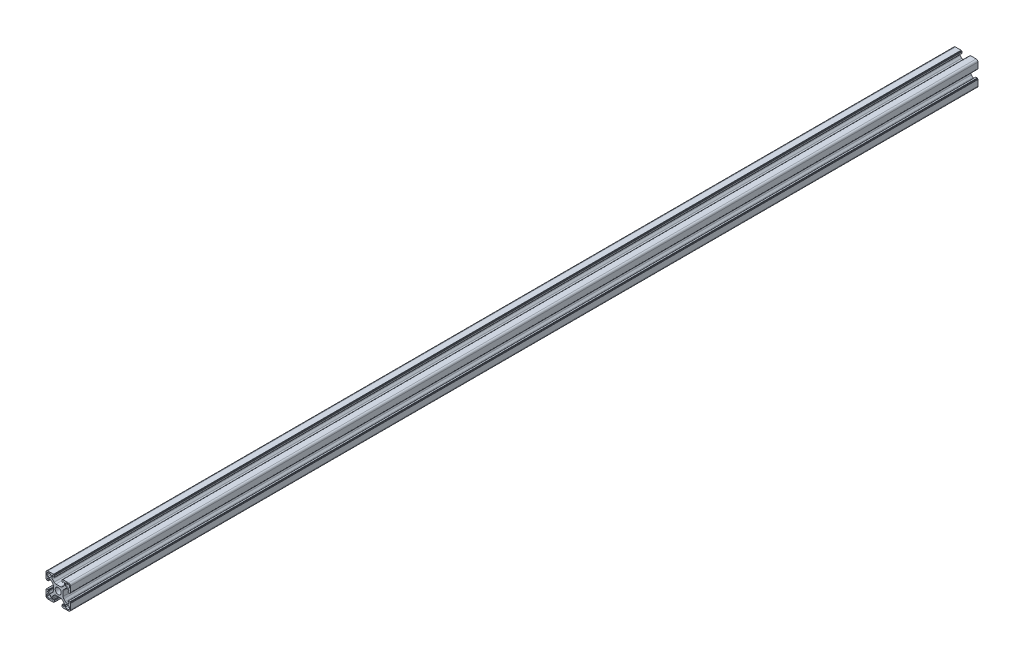
SolidWorks part; units mm, degrees
ref_plane "Спереди" through (0, 0, 0) normal (0, 0, 1) x (1, 0, 0)
ref_plane "Сверху" through (0, 0, 0) normal (0, 1, 0) x (1, 0, 0)
ref_plane "Справа" through (0, 0, 0) normal (1, 0, 0) x (0, 0, -1)
sketch "Эскиз1" plane through (0, 0, 0) normal (0, 0, 1) x (1, 0, 0)
  line L0 (-9.367, 48.5619) -> (-12.367, 45.5619) construction
  line L1 (-18.467, 43.4619) -> (-16.5682, 43.4619)
  line L2 (-18.467, 39.4619) -> (-8.467, 49.4619) construction
  line L3 (-10.867, 47.0619) -> (-12.367, 48.5619) construction
  line L4 (-15.154, 44.0477) -> (-13.8528, 45.3489)
  line L5 (-11.567, 45.5619) -> (-10.167, 45.5619)
  line L6 (-12.367, 46.3619) -> (-12.367, 47.7619)
  line L7 (-10.167, 48.5619) -> (-11.567, 48.5619)
  line L8 (-13.267, 47.6619) -> (-13.267, 46.7631)
  line L9 (-14.7038, 47.5351) -> (-14.2234, 48.0154)
  line L10 (-15.267, 49.0109) -> (-14.767, 49.0109)
  line L11 (-14.8805, 47.4619) -> (-15.167, 47.4619)
  line L12 (-13.8699, 48.1619) -> (-13.767, 48.1619)
  line L13 (-14.767, 49.3119) -> (-14.767, 49.0109)
  line L14 (-15.417, 48.8609) -> (-15.417, 47.7119)
  line L15 (-9.967, 49.4619) -> (-14.617, 49.4619)
  line L16 (-9.367, 47.7619) -> (-9.367, 46.3619)
  line L17 (-8.467, 47.9619) -> (-8.467, 43.3119)
  line L18 (-9.0679, 42.5119) -> (-10.217, 42.5119)
  line L19 (-8.617, 43.1619) -> (-8.9179, 43.1619)
  line L20 (-9.767, 44.059) -> (-9.767, 44.1619)
  line L21 (-10.467, 43.0483) -> (-10.467, 42.7619)
  line L22 (-8.9179, 42.6619) -> (-8.9179, 43.1619)
  line L23 (-10.3938, 43.2251) -> (-9.9134, 43.7054)
  line L24 (-10.267, 44.6619) -> (-11.1658, 44.6619)
  line L25 (-13.8812, 42.7749) -> (-12.58, 44.0761)
  line L26 (-14.467, 39.4619) -> (-14.467, 41.3607)
  line L27 (-14.467, 39.4619) -> (-14.467, 37.5631)
  line L28 (-13.8812, 36.1489) -> (-12.58, 34.8477)
  line L29 (-12.367, 32.5619) -> (-12.367, 31.1619)
  line L30 (-11.567, 33.3619) -> (-10.167, 33.3619)
  line L31 (-9.367, 31.1619) -> (-9.367, 32.5619)
  line L32 (-10.267, 34.2619) -> (-11.1658, 34.2619)
  line L33 (-10.3938, 35.6987) -> (-9.9134, 35.2183)
  line L34 (-8.9179, 36.2619) -> (-8.9179, 35.7619)
  line L35 (-10.467, 35.8754) -> (-10.467, 36.1619)
  line L36 (-9.767, 34.8648) -> (-9.767, 34.7619)
  line L37 (-8.617, 35.7619) -> (-8.9179, 35.7619)
  line L38 (-9.0679, 36.4119) -> (-10.217, 36.4119)
  line L39 (-8.467, 30.9619) -> (-8.467, 35.6119)
  line L40 (-10.167, 30.3619) -> (-11.567, 30.3619)
  line L41 (-9.967, 29.4619) -> (-14.617, 29.4619)
  line L42 (-15.417, 30.0628) -> (-15.417, 31.2119)
  line L43 (-14.767, 29.6119) -> (-14.767, 29.9128)
  line L44 (-13.8699, 30.7619) -> (-13.767, 30.7619)
  line L45 (-14.8805, 31.4619) -> (-15.167, 31.4619)
  line L46 (-15.267, 29.9128) -> (-14.767, 29.9128)
  line L47 (-14.7038, 31.3887) -> (-14.2234, 30.9083)
  line L48 (-13.267, 31.2619) -> (-13.267, 32.1607)
  line L49 (-15.154, 34.8761) -> (-13.8528, 33.5749)
  line L50 (-18.467, 35.4619) -> (-16.5682, 35.4619)
  line L51 (-9.367, 30.3619) -> (-12.367, 33.3619) construction
  line L52 (-18.467, 39.4619) -> (-8.467, 29.4619) construction
  line L53 (-10.867, 31.8619) -> (-9.367, 33.3619) construction
  line L54 (-18.467, 35.4619) -> (-20.3658, 35.4619)
  line L55 (-21.78, 34.8761) -> (-23.0812, 33.5749)
  line L56 (-25.367, 33.3619) -> (-26.767, 33.3619)
  line L57 (-24.567, 32.5619) -> (-24.567, 31.1619)
  line L58 (-26.767, 30.3619) -> (-25.367, 30.3619)
  line L59 (-23.667, 31.2619) -> (-23.667, 32.1607)
  line L60 (-22.2302, 31.3887) -> (-22.7105, 30.9083)
  line L61 (-21.667, 29.9128) -> (-22.167, 29.9128)
  line L62 (-22.0534, 31.4619) -> (-21.767, 31.4619)
  line L63 (-23.0641, 30.7619) -> (-23.167, 30.7619)
  line L64 (-22.167, 29.6119) -> (-22.167, 29.9128)
  line L65 (-21.517, 30.0628) -> (-21.517, 31.2119)
  line L66 (-26.967, 29.4619) -> (-22.317, 29.4619)
  line L67 (-27.567, 31.1619) -> (-27.567, 32.5619)
  line L68 (-28.467, 30.9619) -> (-28.467, 35.6119)
  line L69 (-27.8661, 36.4119) -> (-26.717, 36.4119)
  line L70 (-28.317, 35.7619) -> (-28.0161, 35.7619)
  line L71 (-27.167, 34.8648) -> (-27.167, 34.7619)
  line L72 (-26.467, 35.8754) -> (-26.467, 36.1619)
  line L73 (-28.0161, 36.2619) -> (-28.0161, 35.7619)
  line L74 (-26.5402, 35.6987) -> (-27.0205, 35.2183)
  line L75 (-26.667, 34.2619) -> (-25.7682, 34.2619)
  line L76 (-23.0528, 36.1489) -> (-24.354, 34.8477)
  line L77 (-22.467, 39.4619) -> (-22.467, 37.5631)
  line L78 (-27.567, 30.3619) -> (-24.567, 33.3619) construction
  line L79 (-18.467, 39.4619) -> (-28.467, 29.4619) construction
  line L80 (-26.067, 31.8619) -> (-24.567, 30.3619) construction
  line L81 (-22.467, 39.4619) -> (-22.467, 41.3607)
  line L82 (-23.0528, 42.7749) -> (-24.354, 44.0761)
  line L83 (-24.567, 46.3619) -> (-24.567, 47.7619)
  line L84 (-25.367, 45.5619) -> (-26.767, 45.5619)
  line L85 (-27.567, 47.7619) -> (-27.567, 46.3619)
  line L86 (-26.667, 44.6619) -> (-25.7682, 44.6619)
  line L87 (-26.5402, 43.2251) -> (-27.0205, 43.7054)
  line L88 (-28.0161, 42.6619) -> (-28.0161, 43.1619)
  line L89 (-26.467, 43.0483) -> (-26.467, 42.7619)
  line L90 (-27.167, 44.059) -> (-27.167, 44.1619)
  line L91 (-28.317, 43.1619) -> (-28.0161, 43.1619)
  line L92 (-27.8661, 42.5119) -> (-26.717, 42.5119)
  line L93 (-28.467, 47.9619) -> (-28.467, 43.3119)
  line L94 (-26.767, 48.5619) -> (-25.367, 48.5619)
  line L95 (-26.967, 49.4619) -> (-22.317, 49.4619)
  line L96 (-21.517, 48.8609) -> (-21.517, 47.7119)
  line L97 (-22.167, 49.3119) -> (-22.167, 49.0109)
  line L98 (-23.0641, 48.1619) -> (-23.167, 48.1619)
  line L99 (-22.0534, 47.4619) -> (-21.767, 47.4619)
  line L100 (-21.667, 49.0109) -> (-22.167, 49.0109)
  line L101 (-22.2302, 47.5351) -> (-22.7105, 48.0154)
  line L102 (-23.667, 47.6619) -> (-23.667, 46.7631)
  line L103 (-21.78, 44.0477) -> (-23.0812, 45.3489)
  line L104 (-18.467, 43.4619) -> (-20.3658, 43.4619)
  line L105 (-30.231, 39.4619) -> (-6.9626, 39.4619) construction
  line L106 (-27.567, 48.5619) -> (-24.567, 45.5619) construction
  line L107 (-18.467, 27.3755) -> (-18.467, 50.1808) construction
  line L108 (-18.467, 39.4619) -> (-28.467, 49.4619) construction
  line L109 (-26.067, 47.0619) -> (-27.567, 45.5619) construction
  arc A0 (-9.367, 47.7619) -> (-10.167, 48.5619) centre (-10.167, 47.7619) ccw
  arc A1 (-11.567, 48.5619) -> (-12.367, 47.7619) centre (-11.567, 47.7619) ccw
  arc A2 (-11.567, 45.5619) -> (-12.367, 46.3619) centre (-11.567, 46.3619) cw
  arc A3 (-9.967, 49.4619) -> (-8.467, 47.9619) centre (-9.967, 47.9619) cw
  arc A4 (-15.267, 49.0109) -> (-15.417, 48.8609) centre (-15.267, 48.8609) ccw
  arc A5 (-14.617, 49.4619) -> (-14.767, 49.3119) centre (-14.617, 49.3119) ccw
  arc A6 (-14.8805, 47.4619) -> (-14.7038, 47.5351) centre (-14.8805, 47.7119) ccw
  arc A7 (-15.167, 47.4619) -> (-15.417, 47.7119) centre (-15.167, 47.7119) cw
  arc A8 (-14.2234, 48.0154) -> (-13.8699, 48.1619) centre (-13.8699, 47.6619) cw
  arc A9 (-13.767, 48.1619) -> (-13.267, 47.6619) centre (-13.767, 47.6619) cw
  arc A10 (-15.967, 39.4619) -> (-18.467, 41.9619) centre (-18.467, 39.4619) ccw
  arc A11 (-16.5682, 43.4619) -> (-15.154, 44.0477) centre (-16.5682, 45.4619) ccw
  arc A12 (-13.267, 46.7631) -> (-13.8528, 45.3489) centre (-15.267, 46.7631) cw
  arc A13 (-9.367, 46.3619) -> (-10.167, 45.5619) centre (-10.167, 46.3619) cw
  arc A14 (-9.767, 44.1619) -> (-10.267, 44.6619) centre (-10.267, 44.1619) ccw
  arc A15 (-9.9134, 43.7054) -> (-9.767, 44.059) centre (-10.267, 44.059) ccw
  arc A16 (-10.467, 42.7619) -> (-10.217, 42.5119) centre (-10.217, 42.7619) ccw
  arc A17 (-10.467, 43.0483) -> (-10.3938, 43.2251) centre (-10.217, 43.0483) cw
  arc A18 (-8.467, 43.3119) -> (-8.617, 43.1619) centre (-8.617, 43.3119) cw
  arc A19 (-8.9179, 42.6619) -> (-9.0679, 42.5119) centre (-9.0679, 42.6619) cw
  arc A20 (-11.1658, 44.6619) -> (-12.58, 44.0761) centre (-11.1658, 42.6619) ccw
  arc A21 (-14.467, 41.3607) -> (-13.8812, 42.7749) centre (-12.467, 41.3607) cw
  arc A22 (-10.167, 30.3619) -> (-9.367, 31.1619) centre (-10.167, 31.1619) ccw
  arc A23 (-9.367, 32.5619) -> (-10.167, 33.3619) centre (-10.167, 32.5619) ccw
  arc A24 (-12.367, 32.5619) -> (-11.567, 33.3619) centre (-11.567, 32.5619) cw
  arc A25 (-8.467, 30.9619) -> (-9.967, 29.4619) centre (-9.967, 30.9619) cw
  arc A26 (-8.9179, 36.2619) -> (-9.0679, 36.4119) centre (-9.0679, 36.2619) ccw
  arc A27 (-8.467, 35.6119) -> (-8.617, 35.7619) centre (-8.617, 35.6119) ccw
  arc A28 (-10.467, 35.8754) -> (-10.3938, 35.6987) centre (-10.217, 35.8754) ccw
  arc A29 (-10.467, 36.1619) -> (-10.217, 36.4119) centre (-10.217, 36.1619) cw
  arc A30 (-9.9134, 35.2183) -> (-9.767, 34.8648) centre (-10.267, 34.8648) cw
  arc A31 (-9.767, 34.7619) -> (-10.267, 34.2619) centre (-10.267, 34.7619) cw
  arc A32 (-18.467, 36.9619) -> (-15.967, 39.4619) centre (-18.467, 39.4619) ccw
  arc A33 (-14.467, 37.5631) -> (-13.8812, 36.1489) centre (-12.467, 37.5631) ccw
  arc A34 (-11.1658, 34.2619) -> (-12.58, 34.8477) centre (-11.1658, 36.2619) cw
  arc A35 (-11.567, 30.3619) -> (-12.367, 31.1619) centre (-11.567, 31.1619) cw
  arc A36 (-13.767, 30.7619) -> (-13.267, 31.2619) centre (-13.767, 31.2619) ccw
  arc A37 (-14.2234, 30.9083) -> (-13.8699, 30.7619) centre (-13.8699, 31.2619) ccw
  arc A38 (-15.167, 31.4619) -> (-15.417, 31.2119) centre (-15.167, 31.2119) ccw
  arc A39 (-14.8805, 31.4619) -> (-14.7038, 31.3887) centre (-14.8805, 31.2119) cw
  arc A40 (-14.617, 29.4619) -> (-14.767, 29.6119) centre (-14.617, 29.6119) cw
  arc A41 (-15.267, 29.9128) -> (-15.417, 30.0628) centre (-15.267, 30.0628) cw
  arc A42 (-13.267, 32.1607) -> (-13.8528, 33.5749) centre (-15.267, 32.1607) ccw
  arc A43 (-16.5682, 35.4619) -> (-15.154, 34.8761) centre (-16.5682, 33.4619) cw
  arc A44 (-27.567, 31.1619) -> (-26.767, 30.3619) centre (-26.767, 31.1619) ccw
  arc A45 (-25.367, 30.3619) -> (-24.567, 31.1619) centre (-25.367, 31.1619) ccw
  arc A46 (-25.367, 33.3619) -> (-24.567, 32.5619) centre (-25.367, 32.5619) cw
  arc A47 (-26.967, 29.4619) -> (-28.467, 30.9619) centre (-26.967, 30.9619) cw
  arc A48 (-21.667, 29.9128) -> (-21.517, 30.0628) centre (-21.667, 30.0628) ccw
  arc A49 (-22.317, 29.4619) -> (-22.167, 29.6119) centre (-22.317, 29.6119) ccw
  arc A50 (-22.0534, 31.4619) -> (-22.2302, 31.3887) centre (-22.0534, 31.2119) ccw
  arc A51 (-21.767, 31.4619) -> (-21.517, 31.2119) centre (-21.767, 31.2119) cw
  arc A52 (-22.7105, 30.9083) -> (-23.0641, 30.7619) centre (-23.0641, 31.2619) cw
  arc A53 (-23.167, 30.7619) -> (-23.667, 31.2619) centre (-23.167, 31.2619) cw
  arc A54 (-20.967, 39.4619) -> (-18.467, 36.9619) centre (-18.467, 39.4619) ccw
  arc A55 (-20.3658, 35.4619) -> (-21.78, 34.8761) centre (-20.3658, 33.4619) ccw
  arc A56 (-23.667, 32.1607) -> (-23.0812, 33.5749) centre (-21.667, 32.1607) cw
  arc A57 (-27.567, 32.5619) -> (-26.767, 33.3619) centre (-26.767, 32.5619) cw
  arc A58 (-27.167, 34.7619) -> (-26.667, 34.2619) centre (-26.667, 34.7619) ccw
  arc A59 (-27.0205, 35.2183) -> (-27.167, 34.8648) centre (-26.667, 34.8648) ccw
  arc A60 (-26.467, 36.1619) -> (-26.717, 36.4119) centre (-26.717, 36.1619) ccw
  arc A61 (-26.467, 35.8754) -> (-26.5402, 35.6987) centre (-26.717, 35.8754) cw
  arc A62 (-28.467, 35.6119) -> (-28.317, 35.7619) centre (-28.317, 35.6119) cw
  arc A63 (-28.0161, 36.2619) -> (-27.8661, 36.4119) centre (-27.8661, 36.2619) cw
  arc A64 (-25.7682, 34.2619) -> (-24.354, 34.8477) centre (-25.7682, 36.2619) ccw
  arc A65 (-22.467, 37.5631) -> (-23.0528, 36.1489) centre (-24.467, 37.5631) cw
  arc A66 (-26.767, 48.5619) -> (-27.567, 47.7619) centre (-26.767, 47.7619) ccw
  arc A67 (-27.567, 46.3619) -> (-26.767, 45.5619) centre (-26.767, 46.3619) ccw
  arc A68 (-24.567, 46.3619) -> (-25.367, 45.5619) centre (-25.367, 46.3619) cw
  arc A69 (-28.467, 47.9619) -> (-26.967, 49.4619) centre (-26.967, 47.9619) cw
  arc A70 (-28.0161, 42.6619) -> (-27.8661, 42.5119) centre (-27.8661, 42.6619) ccw
  arc A71 (-28.467, 43.3119) -> (-28.317, 43.1619) centre (-28.317, 43.3119) ccw
  arc A72 (-26.467, 43.0483) -> (-26.5402, 43.2251) centre (-26.717, 43.0483) ccw
  arc A73 (-26.467, 42.7619) -> (-26.717, 42.5119) centre (-26.717, 42.7619) cw
  arc A74 (-27.0205, 43.7054) -> (-27.167, 44.059) centre (-26.667, 44.059) cw
  arc A75 (-27.167, 44.1619) -> (-26.667, 44.6619) centre (-26.667, 44.1619) cw
  arc A76 (-18.467, 41.9619) -> (-20.967, 39.4619) centre (-18.467, 39.4619) ccw
  arc A77 (-22.467, 41.3607) -> (-23.0528, 42.7749) centre (-24.467, 41.3607) ccw
  arc A78 (-25.7682, 44.6619) -> (-24.354, 44.0761) centre (-25.7682, 42.6619) cw
  arc A79 (-25.367, 48.5619) -> (-24.567, 47.7619) centre (-25.367, 47.7619) cw
  arc A80 (-23.167, 48.1619) -> (-23.667, 47.6619) centre (-23.167, 47.6619) ccw
  arc A81 (-22.7105, 48.0154) -> (-23.0641, 48.1619) centre (-23.0641, 47.6619) ccw
  arc A82 (-21.767, 47.4619) -> (-21.517, 47.7119) centre (-21.767, 47.7119) ccw
  arc A83 (-22.0534, 47.4619) -> (-22.2302, 47.5351) centre (-22.0534, 47.7119) cw
  arc A84 (-22.317, 49.4619) -> (-22.167, 49.3119) centre (-22.317, 49.3119) cw
  arc A85 (-21.667, 49.0109) -> (-21.517, 48.8609) centre (-21.667, 48.8609) cw
  arc A86 (-23.667, 46.7631) -> (-23.0812, 45.3489) centre (-21.667, 46.7631) ccw
  arc A87 (-20.3658, 43.4619) -> (-21.78, 44.0477) centre (-20.3658, 45.4619) cw
  point P0 (-18.467, 39.4619)
  point P9 (-18.467, 39.4619)
  point P40 (-9.767, 43.1619)
  point P93 (-14.767, 30.7619)
  point P144 (-14.767, 48.1619)
  point P152 (-9.767, 35.7619)
  point P153 (-18.467, 35.5376)
  point P154 (-18.467, 39.4619)
  point P189 (-27.167, 35.7619)
  point P228 (-22.167, 30.7619)
  point P229 (-22.3912, 39.4619)
  point P230 (-18.467, 39.4619)
  point P268 (-22.167, 48.1619)
  point P273 (-14.5427, 39.4619)
  point P306 (-27.167, 43.1619)
  point P307 (-18.467, 43.3861)
  point P309 (-18.467, 39.4619)
  dimension "D3" = 5
  dimension "D6" = 2
  dimension "D1" = 2
  dimension "D2" = 6
  dimension "D4" = 4
  dimension "D5" = 0.9
extrude "Бобышка-Вытянуть1" add sketch "Эскиз1" along normal blind 745
